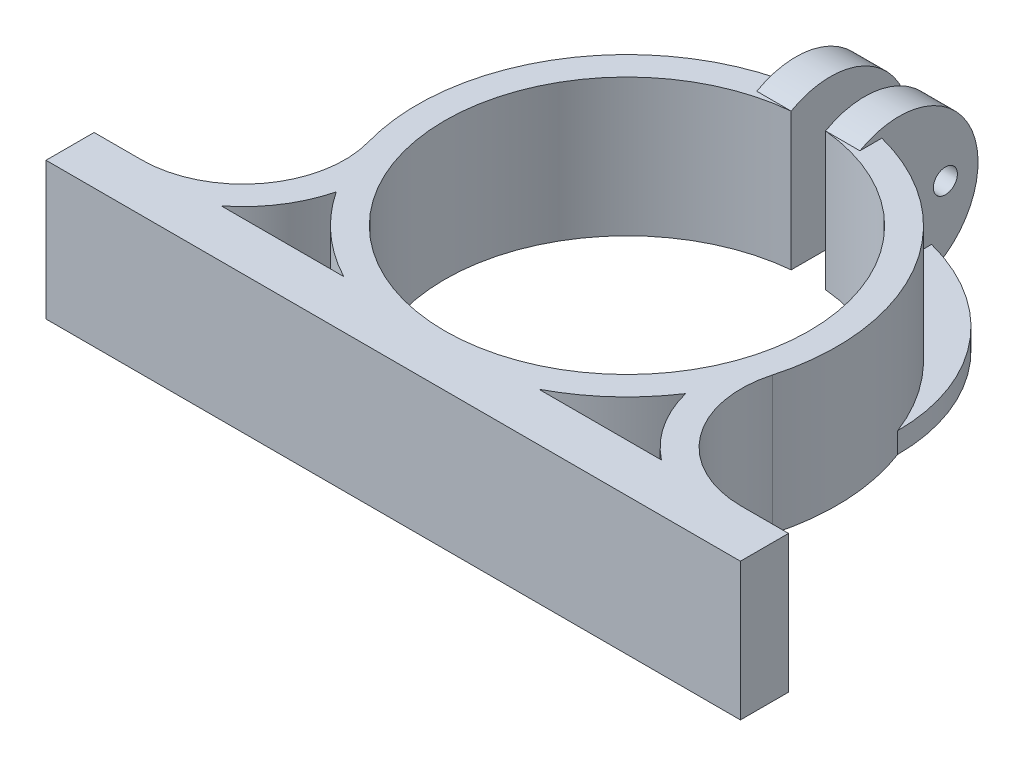
SolidWorks part; units mm, degrees
ref_plane "Alzado" through (0, 0, 0) normal (0, 0, 1) x (1, 0, 0)
ref_plane "Planta" through (0, 0, 0) normal (0, 1, 0) x (1, 0, 0)
ref_plane "Vista lateral" through (0, 0, 0) normal (1, 0, 0) x (0, 0, -1)
sketch "Croquis1" plane through (0, 0, 0) normal (0, 1, 0) x (1, 0, 0)
  line L0 (-50.5, 3.5) -> (50.5, 3.5) construction
  line L1 (-50.5, 0) -> (50.5, 0)
  line L2 (-50.5, 0) -> (-50.5, 7)
  line L3 (-50.5, 7) -> (-43.6, 7)
  line L4 (50.5, 0) -> (50.5, 7)
  line L5 (-2.5, 60.3818) -> (-2.5, 64.3974)
  line L6 (2.5, 60.3818) -> (2.5, 64.3974)
  line L7 (14.1863, 7) -> (32.0138, 7)
  line L8 (43.6, 7) -> (43.6, 0) construction
  line L9 (43.6, 7) -> (50.5, 7)
  line L10 (0, 0) -> (0, 34) construction
  line L11 (-32.0138, 7) -> (-14.1863, 7)
  arc A0 (-2.5, 64.3974) -> (-29.3683, 25.7688) centre (0, 34) ccw
  arc A1 (-2.5, 60.3818) -> (2.5, 60.3818) centre (0, 34) ccw
  arc A2 (14.1863, 7) -> (25.4061, 17.1246) centre (0, 34) ccw
  arc A3 (29.3683, 25.7688) -> (43.6, 7) centre (43.6, 21.7801) ccw
  arc A4 (25.4061, 17.1246) -> (32.0138, 7) centre (43.6, 21.7801) ccw
  arc A5 (-25.4061, 17.1246) -> (-32.0138, 7) centre (-43.6, 21.7801) cw
  arc A6 (-29.3683, 25.7688) -> (-43.6, 7) centre (-43.6, 21.7801) cw
  arc A7 (-25.4061, 17.1246) -> (-14.1863, 7) centre (0, 34) ccw
  arc A8 (29.3683, 25.7688) -> (2.5, 64.3974) centre (0, 34) ccw
  point P10 (0, 60.5)
  dimension "D2" = 101
  dimension "D3" = 61
  dimension "D4" = 53
  dimension "D7" = 6.9
  dimension "D8" = 4
  dimension "D1" = 7
  dimension "D5" = 2.5
  dimension "D6" = 2.5
extrude "Saliente-Extruir1" add sketch "Croquis1" along normal blind 20
sketch "Croquis2" plane through (2.5, 0, 0) normal (-1, 0, 0) x (0, 0, 1)
  line L0 (-64.3974, 0) -> (-25.7688, 0) construction
  line L2 (-60.3818, 20) -> (-60.3818, 0)
  line L3 (-60.3818, 20) -> (-60.3818, 0) construction
  line L4 (-77.5607, 20) -> (-77.5607, 0) construction
  line L5 (-60.3818, 0) -> (-71.7396, 0)
  arc A0 (-60.3818, 20) -> (-71.7396, 0) centre (-66.0607, 10) ccw
  circle A1 centre (-72.8107, 10) radius 1.75
  point P12 (0, 0)
  dimension "D1" = 11.3578
  dimension "D3" = 3.5
  dimension "D5" = 11.5
  dimension "D2" = 10
  dimension "D4" = 4.75
extrude "Saliente-Extruir2" add sketch "Croquis2" against normal blind 5
pattern_linear "MatrizL1" count 2 spacing 10 along (-1, 0, 0) of "Saliente-Extruir2"
sketch "Croquis3" plane through (0, 0, 0) normal (0, 1, 0) x (1, 0, 0)
  line L0 (-7.5, 70.7923) -> (-7.5, 63.5635)
  line L1 (-7.5, 77.5607) -> (-7.5, 60.3818) construction
  line L3 (7.5, 70.7923) -> (7.5, 63.5635)
  line L4 (7.5, 60.3818) -> (7.5, 77.5607) construction
  line L5 (-7.5, 71.7396) -> (7.5, 71.7396) construction
  arc A0 (29.3683, 25.7688) -> (7.5, 63.5635) centre (0, 34) ccw construction
  arc A1 (-7.5, 63.5635) -> (-28.5, 44.8628) centre (0, 34) ccw
  arc A2 (28.5, 44.8628) -> (7.5, 63.5635) centre (0, 34) ccw
  ellipse E0 centre (0, 44.8628) end of major axis (-28.5, 44.8628) minor radius 26.8768 (-7.5, 70.7923) -> (-28.5, 44.8628) ccw
  ellipse E1 centre (0, 44.8628) end of major axis (-28.5, 44.8628) minor radius 26.8768 (28.5, 44.8628) -> (7.5, 70.7923) ccw
  dimension "D2" = 57
extrude "Saliente-Extruir3" add sketch "Croquis3" along normal blind 3
